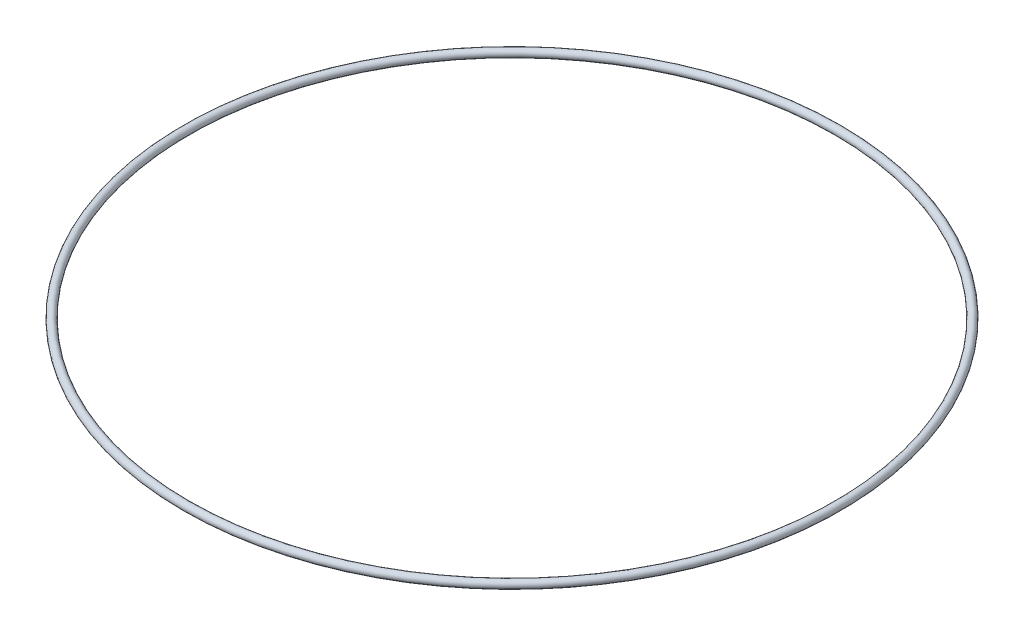
SolidWorks part; units mm, degrees
ref_plane "Front Plane" through (0, 0, 0) normal (0, 0, 1) x (1, 0, 0)
ref_plane "Top Plane" through (0, 0, 0) normal (0, 1, 0) x (1, 0, 0)
ref_plane "Right Plane" through (0, 0, 0) normal (1, 0, 0) x (0, 0, -1)
sketch "Sketch2" plane through (0, 0, 0) normal (1, 0, 0) x (0, 0, -1)
  circle A0 centre (205, 0) radius 2.5
  dimension "D1" = 5
  dimension "D2" = 205
ref_axis "Axis1" through (0, 0, 0) along (0, 1, 0)
revolve "Revolve1" add sketch "Sketch2" angle 360 about axis through (0, 0, 0) along (0, 1, 0)
